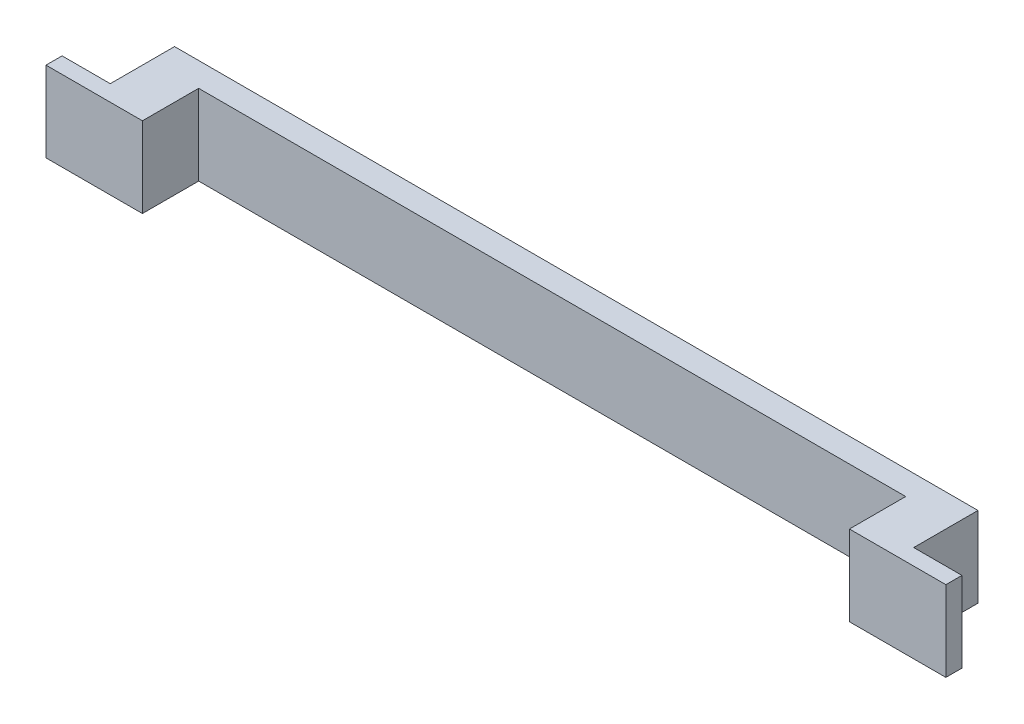
SolidWorks part; units mm, degrees
ref_plane "Front Plane" through (0, 0, 0) normal (0, 0, 1) x (1, 0, 0)
ref_plane "Top Plane" through (0, 0, 0) normal (0, 1, 0) x (1, 0, 0)
ref_plane "Right Plane" through (0, 0, 0) normal (1, 0, 0) x (0, 0, -1)
sketch "Sketch1" plane through (0, 0, 0) normal (0, 1, 0) x (1, 0, 0)
  line L0 (0, 0) -> (0, -6.2121) construction
  line L1 (-22, -1) -> (22, -1)
  line L2 (-25, -0.5) -> (-25, 0.5)
  line L3 (-25, 0.5) -> (25, 0.5)
  line L4 (25, -0.5) -> (25, 0.5)
  line L5 (-25, -0.5) -> (25, 0.5) construction
  line L6 (-25, 0.5) -> (25, -0.5) construction
  line L7 (22, -1) -> (22, -4.5)
  line L8 (25, -4.5) -> (22, -4.5)
  line L9 (-25, -0.5) -> (-25, -4.5)
  line L10 (-25, -4.5) -> (-22, -4.5)
  line L11 (-22, -1) -> (-22, -4.5)
  line L12 (25, -0.5) -> (25, -4.5)
  point P0 (0, 0)
  dimension "D1" = 50
  dimension "D2" = 1
  dimension "D3" = 4
  dimension "D4" = 3
  dimension "D5" = 1.5
extrude "Boss-Extrude1" add sketch "Sketch1" along normal blind 5
sketch "Sketch2" plane through (0, 0, 4.5) normal (0, 0, 1) x (1, 0, 0)
  line L0 (-25, 5) -> (-22, 5) construction
  line L1 (-22, 0) -> (-28, 0)
  line L2 (-22, 0) -> (-22, 5)
  line L3 (-22, 5) -> (-28, 5)
  line L4 (-28, 0) -> (-28, 5)
  dimension "D1" = 6
extrude "Boss-Extrude2" add sketch "Sketch2" against normal blind 1
mirror "Mirror1" about plane through (0, 0, 0) normal (1, 0, 0) of "Boss-Extrude2"
